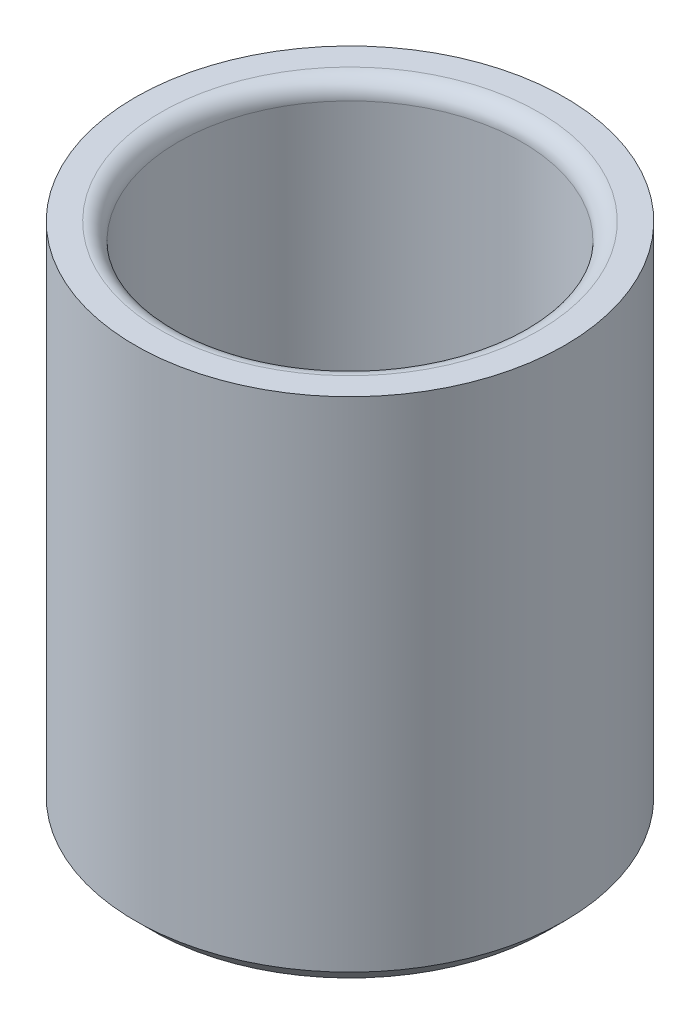
SolidWorks part; units mm, degrees
material "TOOL STEEL"
ref_plane "Front Plane" through (0, 0, 0) normal (0, 0, 1) x (1, 0, 0)
ref_plane "Top Plane" through (0, 0, 0) normal (0, 1, 0) x (1, 0, 0)
ref_plane "Right Plane" through (0, 0, 0) normal (1, 0, 0) x (0, 0, -1)
sketch "BODY SECTION" plane through (0, 0, 0) normal (0, 0, 1) x (1, 0, 0)
  line L0 (0, 0) -> (0, -19.05) construction
  line L1 (6.35, 0) -> (7.9375, 0)
  line L2 (6.35, 0) -> (6.35, -19.05)
  line L3 (6.35, -19.05) -> (7.9375, -19.05)
  line L4 (7.9375, 0) -> (7.9375, -19.05)
  dimension "LENGTH" = 19.05
  dimension "ID" = 12.7
  dimension "OD" = 15.875
revolve "BODY" add sketch "BODY SECTION" angle 360 about L0
fillet "TOP RADIUS" radius 0.635 1 edges at (-6.35, 0, 0)
chamfer "BOTTOM CHAMFER" distance 0.635 angle 45 1 edges at (-7.9375, -19.05, 0)
